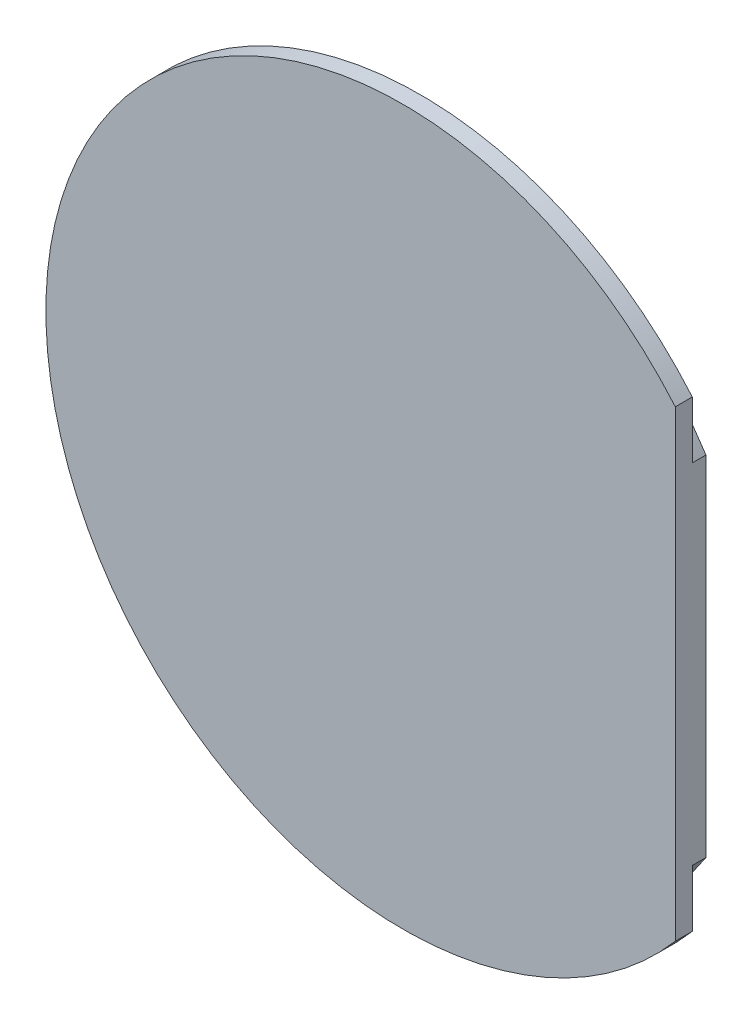
SolidWorks part; units mm, degrees
ref_plane "Front Plane" through (0, 0, 0) normal (0, 0, 1) x (1, 0, 0)
ref_plane "Top Plane" through (0, 0, 0) normal (0, 1, 0) x (1, 0, 0)
ref_plane "Right Plane" through (0, 0, 0) normal (1, 0, 0) x (0, 0, -1)
sketch "Sketch1" plane through (0, 0, 0) normal (0, 0, 1) x (1, 0, 0)
  circle A0 centre (0, 0) radius 21
extrude "Boss-Extrude1" add sketch "Sketch1" along normal blind 1 from offset 27
sketch "Sketch2" plane through (0, 0, 0) normal (0, 0, 1) x (1, 0, 0)
  circle A0 centre (0, 0) radius 19
extrude "Boss-Extrude2" add sketch "Sketch2" along normal blind 0.8 from offset 27.8
sketch "Sketch3" plane through (0, 0, 0) normal (0, 0, 1) x (1, 0, 0)
  line L0 (16, -30) -> (30, -30)
  line L1 (30, -30) -> (30, 30)
  line L2 (30, 30) -> (16, 30)
  line L3 (16, 30) -> (16, -30)
extrude "Cut-Extrude1" cut sketch "Sketch3" against normal through all and the other way through all
